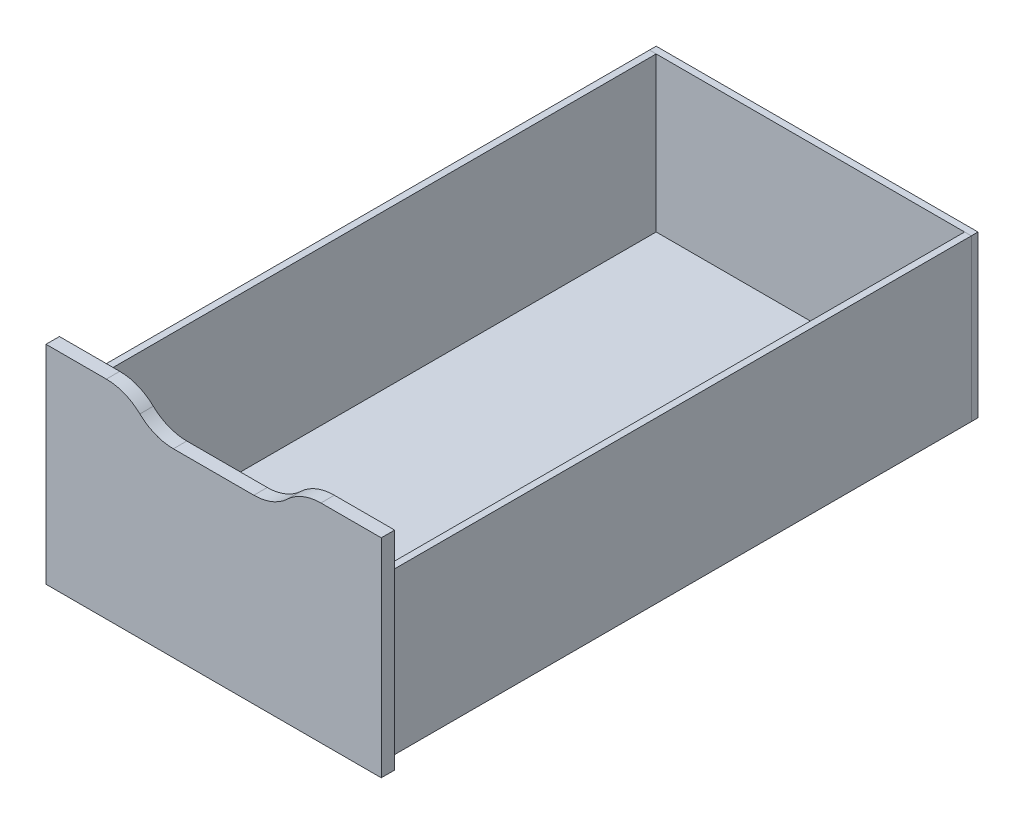
SolidWorks part; units mm, degrees
other "Bottom panel"
other "Front panel"
other "Right panel"
other "Left panel"
other "Back panel"
material "Beech"
ref_plane "Front Plane" through (0, 0, 0) normal (0, 0, 1) x (1, 0, 0)
ref_plane "Top Plane" through (0, 0, 0) normal (0, 1, 0) x (1, 0, 0)
ref_plane "Right Plane" through (0, 0, 0) normal (1, 0, 0) x (0, 0, -1)
sketch "Sketch1" plane through (0, 0, 0) normal (0, 1, 0) x (1, 0, 0)
  line L0 (-146.05, 273.05) -> (146.05, 273.05)
  line L1 (-146.05, -279.4) -> (146.05, -279.4)
  line L2 (-146.05, -279.4) -> (-146.05, 273.05)
  line L3 (-146.05, 279.4) -> (146.05, 279.4) construction
  line L4 (146.05, -279.4) -> (146.05, 273.05)
  line L5 (-146.05, -279.4) -> (146.05, 279.4) construction
  line L6 (-146.05, 279.4) -> (146.05, -279.4) construction
  line L7 (-146.05, 273.05) -> (-146.05, 279.4) construction
  line L8 (146.05, 273.05) -> (146.05, 279.4) construction
  point P0 (0, 0)
  dimension "D1" = 292.1
  dimension "D2" = 558.8
  dimension "D3" = 6.35
extrude "Boss-Extrude1" add sketch "Sketch1" along normal blind 6.35
sketch "Sketch2" plane through (0, 0, 279.4) normal (0, 0, 1) x (1, 0, 0)
  line L0 (-146.05, 0) -> (146.05, 0) construction
  line L1 (-158.75, -6.35) -> (158.75, -6.35)
  line L2 (-158.75, -6.35) -> (-158.75, 190.5)
  line L3 (-158.75, 190.5) -> (158.75, 190.5)
  line L4 (158.75, -6.35) -> (158.75, 190.5)
  point P4 (0, -6.35)
  dimension "D1" = 317.5
  dimension "D2" = 196.85
  dimension "D3" = 6.35
extrude "Boss-Extrude2" add sketch "Sketch2" along normal blind 12.7 separate body
sketch "Sketch3" plane through (0, 0, 292.1) normal (0, 0, 1) x (1, 0, 0)
  line L0 (-101.6, 203.2) -> (101.6, 203.2)
  line L1 (101.6, 203.2) -> (101.6, 190.5)
  line L2 (158.75, 190.5) -> (-158.75, 190.5) construction
  line L3 (38.1, 165.1) -> (-38.1, 165.1)
  line L4 (-101.6, 190.5) -> (-101.6, 203.2)
  arc A0 (101.6, 190.5) -> (69.85, 177.8) centre (101.6, 144.4625) ccw
  arc A1 (69.85, 177.8) -> (38.1, 165.1) centre (38.1, 211.1375) cw
  arc A2 (-38.1, 165.1) -> (-69.85, 177.8) centre (-38.1, 211.1375) cw
  arc A3 (-69.85, 177.8) -> (-101.6, 190.5) centre (-101.6, 144.4625) ccw
  point P15 (0, 203.2)
  point P17 (0, 165.1)
  dimension "D1" = 203.2
  dimension "D2" = 25.4
  dimension "D3" = 12.7
  dimension "D4" = 76.2
extrude "Cut-Extrude1" cut sketch "Sketch3" against normal through all
sketch "Sketch4" plane through (146.05, 0, 0) normal (1, 0, 0) x (0, 0, -1)
  line L0 (-279.4, 6.35) -> (-279.4, 0) construction
  line L1 (-279.4, 0) -> (273.05, 0)
  line L2 (-279.4, 0) -> (-279.4, 152.4)
  line L3 (-279.4, 152.4) -> (273.05, 152.4)
  line L4 (273.05, 0) -> (273.05, 152.4)
  line L5 (-279.4, 0) -> (273.05, 0) construction
  line L6 (273.05, 6.35) -> (273.05, 0) construction
  line L8 (-292.1, 190.5) -> (-279.4, 190.5) construction
  dimension "D1" = 38.1
extrude "Boss-Extrude3" add sketch "Sketch4" along normal blind 6.35 separate body
mirror "Mirror2" about plane through (0, 0, 0) normal (1, 0, 0) of bodies 104
sketch "Sketch5" plane through (0, 0, -273.05) normal (0, 0, -1) x (-1, 0, 0)
  line L0 (-146.05, 0) -> (146.05, 0) construction
  line L1 (-152.4, 0) -> (152.4, 0)
  line L2 (-152.4, 0) -> (-152.4, 152.4)
  line L3 (-152.4, 152.4) -> (152.4, 152.4)
  line L4 (152.4, 0) -> (152.4, 152.4)
  line L5 (-152.4, 0) -> (-152.4, 152.4) construction
  line L6 (-152.4, 152.4) -> (-146.05, 152.4) construction
  line L7 (152.4, 0) -> (152.4, 152.4) construction
extrude "Boss-Extrude4" add sketch "Sketch5" along normal blind 6.35 separate body
